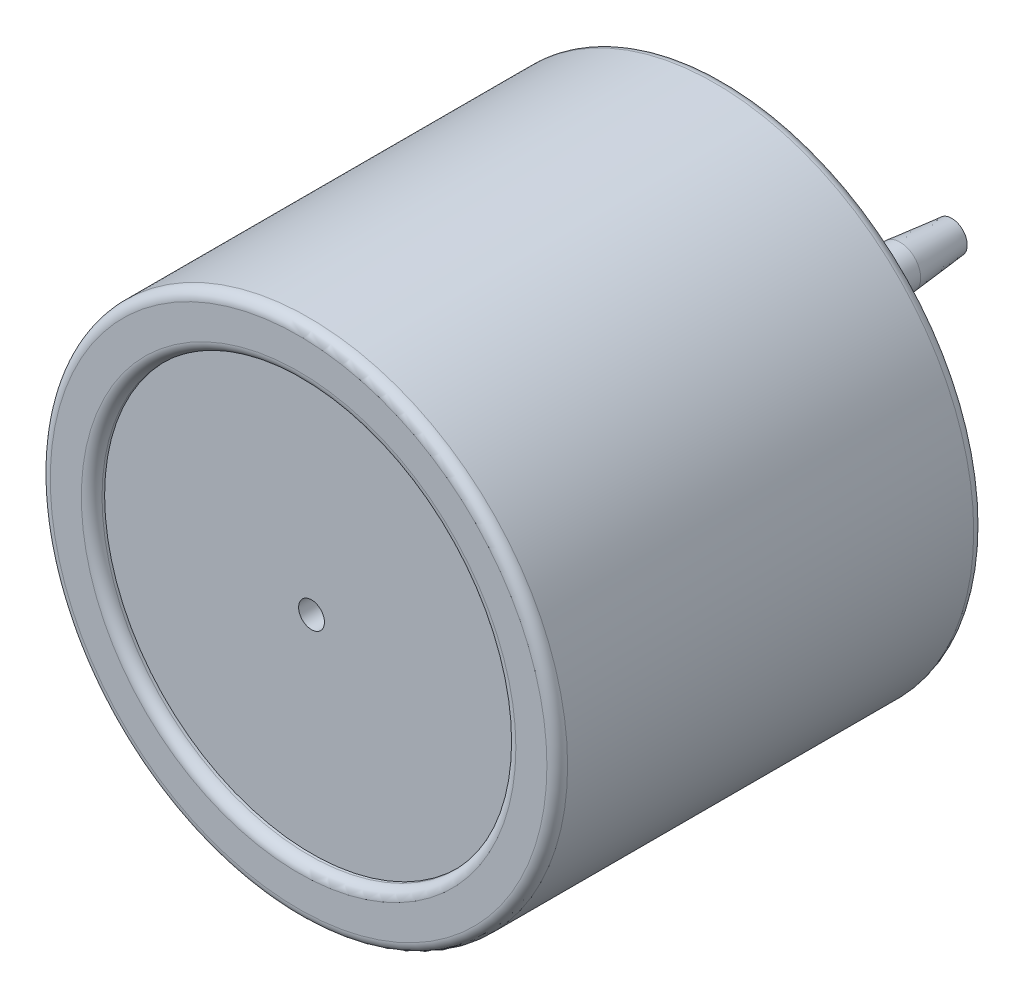
SolidWorks part; units mm, degrees
ref_plane "Спереди" through (0, 0, 0) normal (0, 0, 1) x (1, 0, 0)
ref_plane "Сверху" through (0, 0, 0) normal (0, 1, 0) x (1, 0, 0)
ref_plane "Справа" through (0, 0, 0) normal (1, 0, 0) x (0, 0, -1)
sketch "Эскиз1" plane through (0, 0, 0) normal (0, 0, 1) x (1, 0, 0)
  circle A0 centre (0, 0) radius 10
  dimension "D1" = 20
extrude "Бобышка-Вытянуть1" add sketch "Эскиз1" along normal blind 16.5
sketch "Эскиз2" plane through (0, 0, 16.5) normal (0, 0, 1) x (1, 0, 0)
  circle A0 centre (0, 0) radius 0.5
  dimension "D1" = 1
extrude "Вырез-Вытянуть1" cut sketch "Эскиз2" against normal blind 6
sketch "Эскиз3" plane through (0, 0, 16.5) normal (0, 0, 1) x (1, 0, 0)
  circle A0 centre (0, 0) radius 8
  dimension "D1" = 16
extrude "Вырез-Вытянуть2" cut sketch "Эскиз3" against normal blind 0.5
sketch "Эскиз4" plane through (0, 0, 0) normal (0, 0, -1) x (-1, 0, 0)
  circle A0 centre (0, 0) radius 8.75
  dimension "D1" = 17.5
extrude "Вырез-Вытянуть3" cut sketch "Эскиз4" against normal blind 0.8
sketch "Эскиз5" plane through (0, 0, 0.8) normal (0, 0, -1) x (-1, 0, 0)
  line L0 (0, 0) -> (0, 10) construction
  circle A0 centre (0, 0) radius 10 construction
  circle A1 centre (-4.7, 5) radius 0.8
  circle A2 centre (4.7, 5) radius 0.8
  dimension "D1" = 1.6
  dimension "D2" = 4.7
  dimension "D3" = 5
extrude "Бобышка-Вытянуть2" add sketch "Эскиз5" along normal blind 4.85
chamfer "Фаска1" distance 2 distance2 0.2 2 edges at (-3.9, 5, -4.05) (3.9, 5, -4.05)
fillet "Скругление1" radius 0.4 4 edges at (10, 0, 0) (-8.75, 0, 0) (10, 0, 16.5) (8, 0, 16.5)
